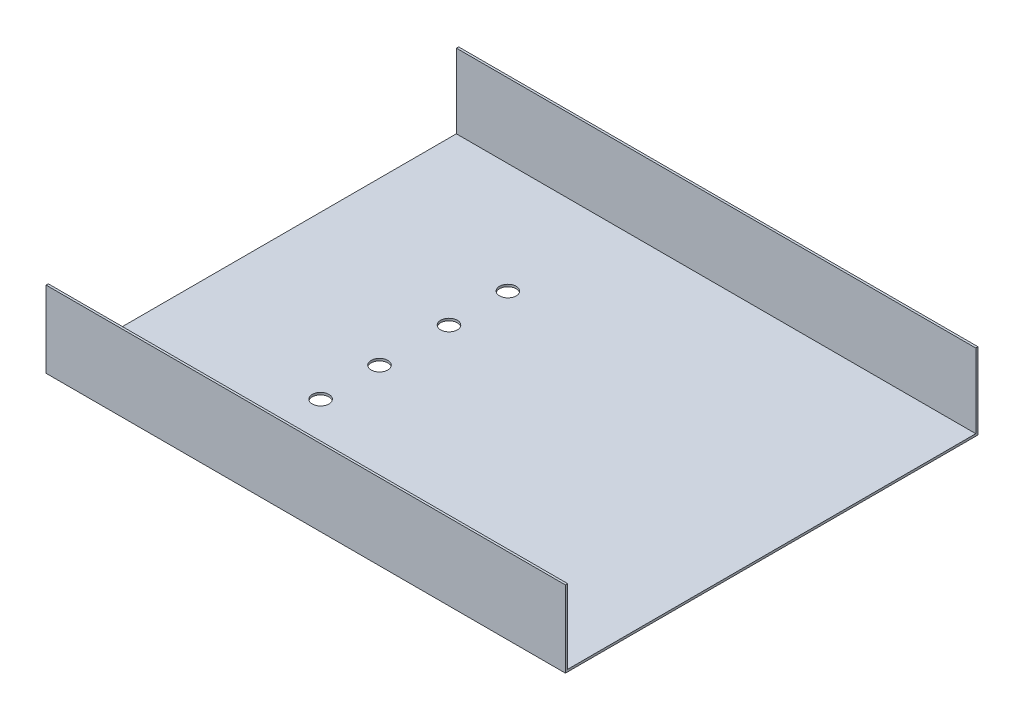
SolidWorks part; units mm, degrees
material "AISI 304"
ref_plane "Alzado" through (0, 0, 0) normal (0, 0, 1) x (1, 0, 0)
ref_plane "Planta" through (0, 0, 0) normal (0, 1, 0) x (1, 0, 0)
ref_plane "Vista lateral" through (0, 0, 0) normal (1, 0, 0) x (0, 0, -1)
sketch "Croquis1" plane through (0, 0, 0) normal (1, 0, 0) x (0, 0, -1)
  line L0 (0, 20) -> (0, 0)
  line L1 (0, 0) -> (110, 0)
  line L2 (110, 0) -> (110, 20)
  line L3 (0, 20) -> (110, 20)
  dimension "D1" = 110
  dimension "D2" = 20
extrude "Saliente-Extruir1" add sketch "Croquis1" along normal blind 140
shell "Vaciado1" thickness 0.6
hole_wizard "Taladro de margen para M42" positions "Croquis4" profile "Croquis5" hole size "M4" standard "Ansi Metric"
sketch "Croquis4" plane through (104.2341, 1, -171.2) normal (0, 1, 0) x (1, 0, 0)
  point P0 (-60.5841, -90.9625)
  point P5 (-60.5841, -106.8375)
  point P8 (-60.5841, -125.5625)
  point P11 (-60.5841, -141.4375)
  point P16 (0, 0)
sketch "Croquis5" plane through (43.65, 1, -80.2375) normal (1, 0, 0) x (0, 0, 1)
  line L0 (0, 0) -> (0, 1.599)
  line L1 (0, 1.599) -> (2.25, 1.599)
  line L2 (2.25, 1.599) -> (2.25, 0)
  line L3 (2.25, 0) -> (0, 0)
  line L4 (0, -6.35) -> (0, 107.95) construction
  dimension "Diámetro de taladro hasta el siguiente" = 4.5
  dimension "Profundidad de taladro hasta el siguiente" = 1.599
